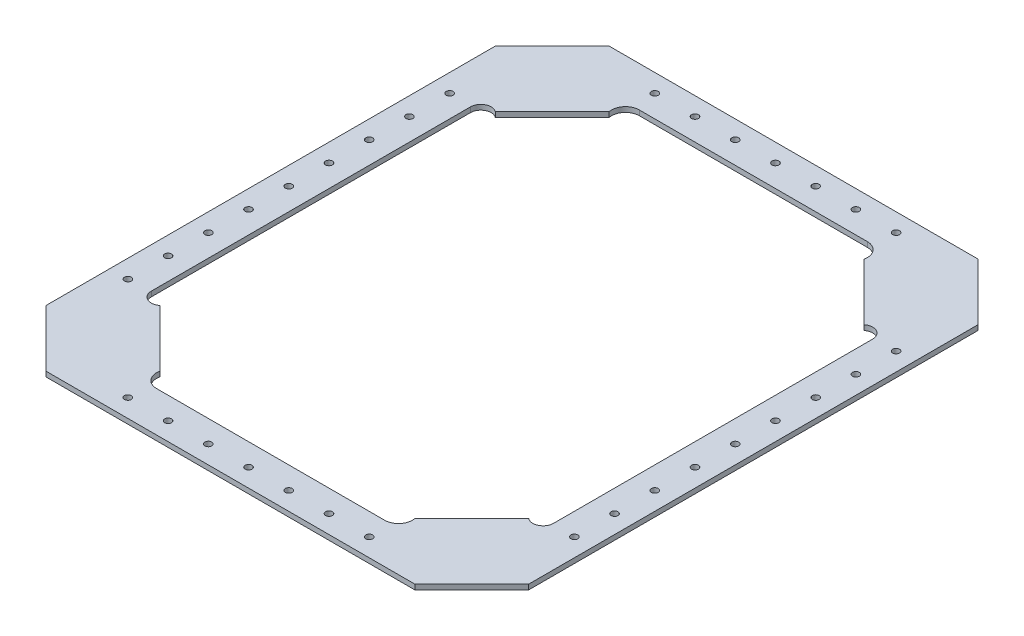
SolidWorks part; units mm, degrees
ref_plane "Front Plane" through (0, 0, 0) normal (0, 0, 1) x (1, 0, 0)
ref_plane "Top Plane" through (0, 0, 0) normal (0, 1, 0) x (1, 0, 0)
ref_plane "Right Plane" through (0, 0, 0) normal (1, 0, 0) x (0, 0, -1)
sketch "Sketch1" plane through (0, 0, 0) normal (0, 1, 0) x (1, 0, 0)
  line L0 (-152.4, 119.0596) -> (-116.479, 154.9807)
  line L1 (-116.479, 154.9807) -> (116.479, 154.9807)
  line L2 (-152.4, 119.0596) -> (-152.4, -164.6983)
  line L3 (152.4, 119.0596) -> (152.4, -164.6983)
  line L4 (152.4, 119.0596) -> (116.479, 154.9807)
  line L5 (0, 154.9807) -> (0, -200.6193) construction
  line L6 (-152.4, -22.8193) -> (152.4, -22.8193) construction
  line L7 (152.4, -164.6983) -> (116.479, -200.6193)
  line L8 (-116.479, -200.6193) -> (116.479, -200.6193)
  line L9 (-152.4, -164.6983) -> (-116.479, -200.6193)
  point P9 (0, -22.8193)
  point P11 (0, -22.8193)
  dimension "D1" = 355.6
  dimension "D3" = 50.8
  dimension "D4" = 135
extrude "Boss-Extrude1" add sketch "Sketch1" along normal blind 3.175
sketch "Sketch2" plane through (0, 3.175, 0) normal (0, 1, 0) x (1, 0, 0)
  line L0 (-152.4, -22.8193) -> (199.0625, -22.8193) construction
  line L1 (-152.4, 119.0596) -> (-152.4, -164.6983) construction
  line L2 (-91.079, 129.5807) -> (91.079, 129.5807)
  line L4 (82.443, 8.9307) -> (-74.315, 8.9307)
  line L6 (-116.479, 154.9807) -> (-91.079, 129.5807) construction
  line L7 (116.479, 154.9807) -> (91.079, 129.5807) construction
  line L8 (116.479, 154.9807) -> (-116.479, 154.9807) construction
  line L9 (-74.315, 8.9307) -> (-127, 8.9307)
  line L10 (-127, 8.9307) -> (-127, 93.6596)
  line L11 (-127, 93.6596) -> (-91.079, 129.5807)
  line L12 (82.443, 8.9307) -> (127, 8.9307)
  line L13 (127, 8.9307) -> (127, 93.6596)
  line L14 (127, 93.6596) -> (91.079, 129.5807)
  line L16 (127, -139.2983) -> (91.079, -175.2193)
  line L17 (127, -54.5693) -> (127, -139.2983)
  line L18 (82.443, -54.5693) -> (127, -54.5693)
  line L19 (-127, -139.2983) -> (-91.079, -175.2193)
  line L20 (-127, -54.5693) -> (-127, -139.2983)
  line L21 (-74.315, -54.5693) -> (-127, -54.5693)
  line L23 (82.443, -54.5693) -> (-74.315, -54.5693)
  line L25 (-91.079, -175.2193) -> (91.079, -175.2193)
  dimension "D1" = 135
  dimension "D2" = 135
  dimension "D3" = 25.4
  dimension "D4" = 90
  dimension "D5" = 90
  dimension "D6" = 50.8
  dimension "D7" = 50.8
  dimension "D8" = 31.75
  dimension "D9" = 25.4
extrude "Cut-Extrude1" cut sketch "Sketch2" against normal through all
sketch "Sketch4" plane through (0, 3.175, 0) normal (0, 1, 0) x (1, 0, 0)
  line L0 (-152.4, -22.8193) -> (171.6111, -22.8193) construction
  line L1 (-152.4, 119.0596) -> (-152.4, -164.6983) construction
  line L2 (116.479, 154.9807) -> (-116.479, 154.9807) construction
  line L3 (0, -22.8193) -> (0, -217.7016) construction
  line L4 (152.4, -164.6983) -> (152.4, 119.0596) construction
  line L5 (0, -22.8193) -> (0, 293.0757) construction
  circle A0 centre (0, 143.5507) radius 2.159
  circle A1 centre (-50.8, 143.5507) radius 2.159
  circle A2 centre (50.8, 143.5507) radius 2.159
  circle A3 centre (-25.4, 143.5507) radius 2.159
  circle A4 centre (25.4, 143.5507) radius 2.159
  circle A5 centre (-140.97, -22.8193) radius 2.159
  circle A6 centre (-140.97, 2.5807) radius 2.159
  circle A7 centre (-140.97, 27.9807) radius 2.159
  circle A8 centre (140.97, -22.8193) radius 2.159
  circle A9 centre (140.97, 2.5807) radius 2.159
  circle A10 centre (140.97, 27.9807) radius 2.159
  circle A11 centre (140.97, -73.6193) radius 2.159
  circle A12 centre (140.97, -48.2193) radius 2.159
  circle A13 centre (-140.97, -73.6193) radius 2.159
  circle A14 centre (-140.97, -48.2193) radius 2.159
  circle A15 centre (25.4, -189.1893) radius 2.159
  circle A16 centre (-25.4, -189.1893) radius 2.159
  circle A17 centre (50.8, -189.1893) radius 2.159
  circle A18 centre (-50.8, -189.1893) radius 2.159
  circle A19 centre (0, -189.1893) radius 2.159
  circle A20 centre (-76.2, 143.5507) radius 2.159
  circle A21 centre (76.2, 143.5507) radius 2.159
  circle A22 centre (-140.97, 53.3807) radius 2.159
  circle A23 centre (140.97, 53.3807) radius 2.159
  circle A24 centre (140.97, -99.0193) radius 2.159
  circle A25 centre (76.2, -189.1893) radius 2.159
  circle A26 centre (-76.2, -189.1893) radius 2.159
  circle A27 centre (-140.97, -99.0193) radius 2.159
  circle A28 centre (-140.97, -124.4193) radius 2.159
  circle A29 centre (-140.97, 78.7807) radius 2.159
  circle A30 centre (140.97, 78.7807) radius 2.159
  circle A31 centre (140.97, -124.4193) radius 2.159
  point P48 (0, 154.9807)
  dimension "D1" = 4.318
  dimension "D2" = 4.318
  dimension "D3" = 4.318
  dimension "D4" = 4.318
  dimension "D5" = 4.318
  dimension "D6" = 4.318
  dimension "D7" = 4.318
  dimension "D8" = 4.318
  dimension "D9" = 4.318
  dimension "D10" = 4.318
  dimension "D11" = 4.318
  dimension "D23" = 4.318
  dimension "D24" = 4.318
  dimension "D27" = 4.318
  dimension "D28" = 4.318
  dimension "D31" = 4.318
  dimension "D12" = 25.4
  dimension "D13" = 25.4
  dimension "D14" = 25.4
  dimension "D15" = 25.4
  dimension "D16" = 25.4
  dimension "D17" = 25.4
  dimension "D18" = 25.4
  dimension "D19" = 25.4
  dimension "D20" = 11.43
  dimension "D21" = 11.43
  dimension "D22" = 11.43
  dimension "D25" = 25.4
  dimension "D26" = 25.4
  dimension "D29" = 25.4
  dimension "D30" = 25.4
  dimension "D32" = 25.4
sketch "Sketch5" plane through (0, 3.175, 0) normal (0, 1, 0) x (1, 0, 0)
  line L0 (-116.479, 83.1386) -> (-80.558, 119.0596)
  line L1 (0, 129.5807) -> (0, -138.0704) construction
  line L3 (-152.4, 119.0596) -> (-152.4, 65.2582)
  line L4 (-127, 93.6596) -> (-127, 8.9307) construction
  line L5 (91.079, 129.5807) -> (-91.079, 129.5807) construction
  line L6 (-116.479, 154.9807) -> (-59.329, 154.9807)
  line L7 (116.479, 154.9807) -> (-116.479, 154.9807) construction
  line L8 (-59.329, 154.9807) -> (-59.329, 129.5807)
  line L9 (-152.4, 119.0596) -> (-116.479, 154.9807)
  line L10 (-152.4, 119.0596) -> (-152.4, -164.6983) construction
  line L12 (-152.4, 65.2582) -> (-127, 65.2582)
  line L13 (-59.329, 129.5807) -> (-72.029, 129.5807)
  line L14 (127, 65.2582) -> (127, 77.9582)
  line L15 (152.4, -22.8193) -> (-208.2375, -22.8193) construction
  line L16 (152.4, -164.6983) -> (152.4, 119.0596) construction
  line L17 (59.329, 129.5807) -> (72.029, 129.5807)
  line L18 (-127, 65.2582) -> (-127, 77.9582)
  line L19 (152.4, 65.2582) -> (127, 65.2582)
  line L20 (152.4, 119.0596) -> (116.479, 154.9807)
  line L21 (59.329, 154.9807) -> (59.329, 129.5807)
  line L22 (116.479, 154.9807) -> (59.329, 154.9807)
  line L24 (152.4, 119.0596) -> (152.4, 65.2582)
  line L25 (116.479, 83.1386) -> (80.558, 119.0596)
  line L26 (116.479, -128.7773) -> (80.558, -164.6983)
  line L27 (152.4, -164.6983) -> (152.4, -110.8969)
  line L28 (116.479, -200.6193) -> (59.329, -200.6193)
  line L29 (59.329, -200.6193) -> (59.329, -175.2193)
  line L30 (152.4, -164.6983) -> (116.479, -200.6193)
  line L31 (152.4, -110.8969) -> (127, -110.8969)
  line L32 (-127, -110.8969) -> (-127, -123.5969)
  line L33 (59.329, -175.2193) -> (72.029, -175.2193)
  line L34 (127, -110.8969) -> (127, -123.5969)
  line L35 (-59.329, -175.2193) -> (-72.029, -175.2193)
  line L36 (-152.4, -110.8969) -> (-127, -110.8969)
  line L37 (-152.4, -164.6983) -> (-116.479, -200.6193)
  line L38 (-59.329, -200.6193) -> (-59.329, -175.2193)
  line L39 (-116.479, -200.6193) -> (-59.329, -200.6193)
  line L40 (-152.4, -164.6983) -> (-152.4, -110.8969)
  line L41 (-116.479, -128.7773) -> (-80.558, -164.6983)
  arc A0 (-72.029, 129.5807) -> (-80.558, 119.0596) centre (-72.029, 120.8631) ccw
  arc A1 (-127, 77.9582) -> (-116.479, 83.1386) centre (-120.4641, 77.9582) cw
  arc A2 (127, 77.9582) -> (116.479, 83.1386) centre (120.4641, 77.9582) ccw
  arc A3 (72.029, 129.5807) -> (80.558, 119.0596) centre (72.029, 120.8631) cw
  arc A4 (72.029, -175.2193) -> (80.558, -164.6983) centre (72.029, -166.5018) ccw
  arc A5 (127, -123.5969) -> (116.479, -128.7773) centre (120.4641, -123.5969) cw
  arc A6 (-127, -123.5969) -> (-116.479, -128.7773) centre (-120.4641, -123.5969) ccw
  arc A7 (-72.029, -175.2193) -> (-80.558, -164.6983) centre (-72.029, -166.5018) cw
  dimension "D3" = 12.7
  dimension "D1" = 50.8
  dimension "D2" = 50.8
  dimension "D4" = 12.7
  dimension "D5" = 57.15
  dimension "D6" = 53.8014
extrude "Boss-Extrude2" add sketch "Sketch5" against normal blind 3.175
extrude "Cut-Extrude2" cut sketch "Sketch4" against normal through all
sketch "Sketch6" plane through (0, 3.175, 0) normal (0, 1, 0) x (1, 0, 0)
  line L0 (-127, 77.9582) -> (-127, 8.9307) construction
  line L1 (-127, 27.2649) -> (127, 27.2649)
  line L2 (-127, 27.2649) -> (-127, -79.6155)
  line L3 (-127, -79.6155) -> (127, -79.6155)
  line L4 (127, 27.2649) -> (127, -79.6155)
  line L5 (127, 8.9307) -> (127, 77.9582) construction
extrude "Cut-Extrude3" cut sketch "Sketch6" against normal through all
